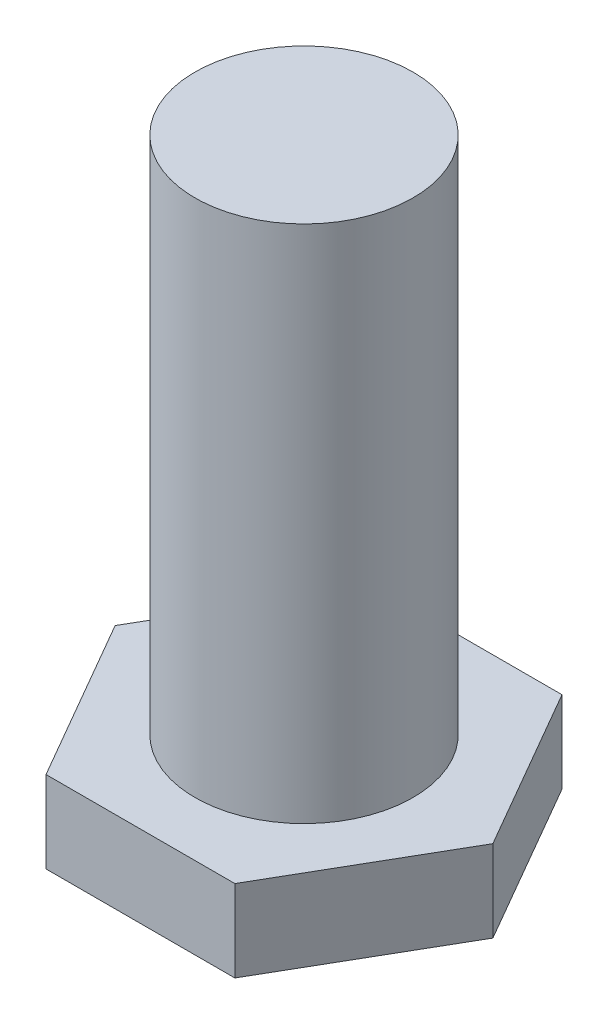
SolidWorks part; units mm, degrees
ref_plane "Alzado" through (0, 0, 0) normal (0, 0, 1) x (1, 0, 0)
ref_plane "Planta" through (0, 0, 0) normal (0, 1, 0) x (1, 0, 0)
ref_plane "Vista lateral" through (0, 0, 0) normal (1, 0, 0) x (0, 0, -1)
sketch "Croquis1" plane through (0, 0, 0) normal (0, 1, 0) x (1, 0, 0)
  line L1 (6.9282, 0) -> (3.4641, 6)
  line L2 (3.4641, 6) -> (-3.4641, 6)
  line L3 (-3.4641, 6) -> (-6.9282, 0)
  line L4 (-6.9282, 0) -> (-3.4641, -6)
  line L5 (-3.4641, -6) -> (3.4641, -6)
  line L6 (3.4641, -6) -> (6.9282, 0)
  circle A0 centre (0, 0) radius 4 construction
  circle A1 centre (0, 0) radius 6 construction
  dimension "D1" = 8
  dimension "D2" = 12
extrude "Saliente-Extruir1" add sketch "Croquis1" along normal blind 3
sketch "Croquis2" plane through (0, 3, 0) normal (0, 1, 0) x (1, 0, 0)
  circle A0 centre (0, 0) radius 4
  dimension "D1" = 8
extrude "Saliente-Extruir2" add sketch "Croquis2" along normal blind 19.05
